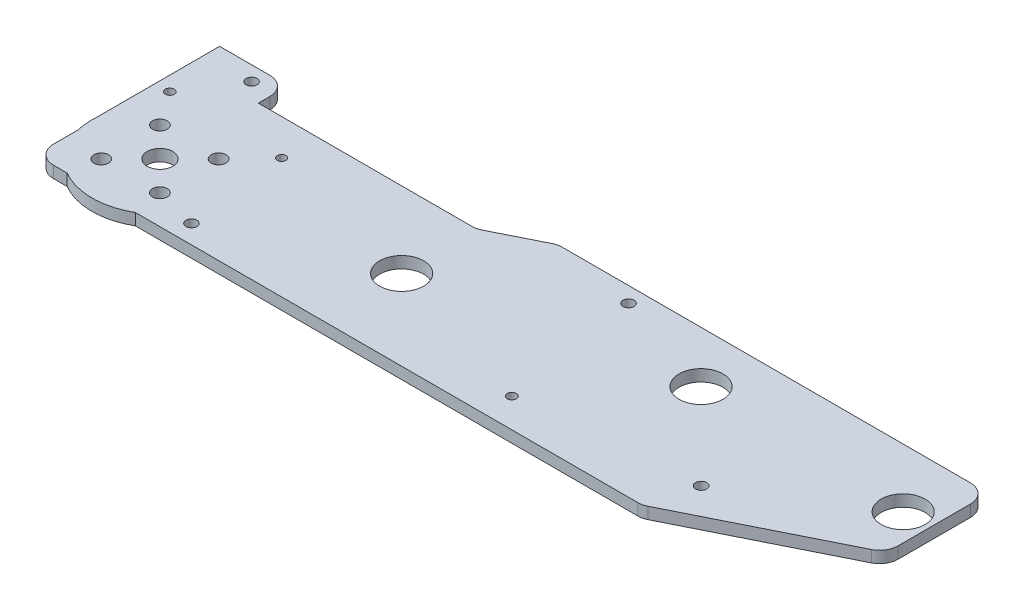
SolidWorks part; units mm, degrees
ref_plane "Front" through (0, 0, 0) normal (0, 0, 1) x (1, 0, 0)
ref_plane "Top" through (0, 0, 0) normal (0, 1, 0) x (1, 0, 0)
ref_plane "Right" through (0, 0, 0) normal (1, 0, 0) x (0, 0, -1)
sketch "Sketch1" plane through (0, 0, 0) normal (0, 1, 0) x (1, 0, 0)
  line L1 (0, 0) -> (210, 0)
  line L2 (0, 0) -> (0, -50)
  line L3 (0, -50) -> (210, -50)
  line L4 (210, 0) -> (210, -50)
  circle A7 centre (3.4895, -16.7877) radius 1.2117
  circle A8 centre (34.3726, -17.194) radius 1.1656
  circle A9 centre (37.5207, -44.9212) radius 1.5
  circle A10 centre (122, -42.0581) radius 1.25
  circle A12 centre (168.9752, -37.4032) radius 1.5173
  circle A13 centre (18, -34) radius 3.4
  dimension "D1" = 210
  dimension "D2" = 50
extrude "Boss-Extrude1" add sketch "Sketch1" along normal blind 3.175
sketch "Sketch2" plane through (0, 3.175, 0) normal (0, 1, 0) x (1, 0, 0)
  line L0 (210, 0) -> (0, 0) construction
  line L1 (0, 0) -> (0, -50) construction
  circle A0 centre (10, -26) radius 2
  circle A1 centre (10, -42) radius 2
  circle A2 centre (26, -26) radius 2
  circle A3 centre (26, -42) radius 2
  dimension "D1" = 16
  dimension "D2" = 16
  dimension "D3" = 16
  dimension "D4" = 26
  dimension "D5" = 10
  dimension "D6" = 10
  dimension "D7" = 26
  dimension "D8" = 16
extrude "Cut-Extrude1" cut sketch "Sketch2" against normal blind 10
sketch "Sketch3" plane through (0, 3.175, 0) normal (0, 1, 0) x (1, 0, 0)
  line L0 (210, 0) -> (0, 0) construction
  line L1 (210, 0) -> (0, 0) construction
  circle A0 centre (78.0103, -28.1) radius 6
  circle A1 centre (145.5313, -14) radius 6
  circle A2 centre (18, -34) radius 0.587
  circle A3 centre (26, -26) radius 2 construction
  circle A4 centre (202.6463, -16) radius 6
  dimension "D1" = 28.1
  dimension "D3" = 16
  dimension "D4" = 14
  dimension "D7" = 125.222
  dimension "D2" = 60.2996
  dimension "D5" = 8
  dimension "D6" = 8
  dimension "D8" = 57.15
extrude "Cut-Extrude2" cut sketch "Sketch3" against normal blind 57.15
sketch "Sketch4" [suppressed] plane through (0, 3.175, 0) normal (0, 1, 0) x (1, 0, 0)
  line L0 (3.4895, -16.7877) -> (18, -34)
  line L1 (3.4895, -20.6627) -> (5.9498, -23.5811)
  line L2 (18, -34) -> (34.3726, -17.194)
  line L3 (34.3726, -17.194) -> (75.8499, -28.1)
  line L4 (75.8499, -28.1) -> (37.5207, -44.9212)
  line L5 (7.3432, -17.194) -> (9.8664, -20.303)
  circle A0 centre (18, -34) radius 15.9299
  circle A1 centre (3.4895, -16.7877) radius 3.8751
  circle A2 centre (34.3726, -17.194) radius 3.7227
  circle A3 centre (37.5207, -44.9212) radius 3.8676
  circle A4 centre (75.8499, -28.1) radius 12.797
  circle A5 centre (112.3021, -4.7393) radius 5.1588
  circle A6 centre (118.879, -40.0177) radius 4.9035
  circle A7 centre (140.772, -16) radius 12.6375
  circle A8 centre (168.9752, -37.4032) radius 4.2066
  circle A9 centre (197.922, -16) radius 12.8
sketch "Sketch5" [suppressed] plane through (0, 3.175, 0) normal (0, 1, 0) x (1, 0, 0)
  line L0 (210, 0) -> (0, 0) construction
  line L2 (-0.6266, -16.7877) -> (37.5207, -16.7877)
  line L3 (-0.6266, -16.7877) -> (-0.6266, -44.9212)
  line L4 (-0.6266, -44.9212) -> (37.5207, -44.9212)
  line L5 (37.5207, -16.7877) -> (37.5207, -44.9212)
  line L6 (75.8499, -15.182) -> (37.5207, -15.182)
  line L7 (75.8499, -15.182) -> (75.8499, -44.9212)
  line L8 (75.8499, -44.9212) -> (37.5207, -44.9212)
  line L9 (37.5207, -15.182) -> (37.5207, -44.9212)
  line L10 (112.3021, -4.7393) -> (75.8499, -4.7393)
  line L11 (112.3021, -4.7393) -> (112.3021, -44.9212)
  line L12 (112.3021, -44.9212) -> (75.8499, -44.9212)
  line L13 (75.8499, -4.7393) -> (75.8499, -44.9212)
  line L14 (112.3021, -4.7393) -> (102.3945, -4.7393)
  line L16 (112.3021, -4.7393) -> (112.3021, 0)
  line L17 (112.3021, 0) -> (102.3945, 0)
  line L18 (102.3945, -4.7393) -> (102.3945, 0)
  line L19 (210, -50) -> (210, 0) construction
  line L20 (112.3021, -4.7393) -> (123.1553, -4.7393)
  line L21 (112.3021, -4.7393) -> (112.3021, 0)
  line L22 (112.3021, 0) -> (123.1553, 0)
  line L23 (123.1553, -4.7393) -> (123.1553, 0)
  line L24 (112.3021, -4.7393) -> (140.772, -4.7393)
  line L25 (112.3021, -4.7393) -> (112.3021, -40.0177)
  line L26 (112.3021, -40.0177) -> (140.772, -40.0177)
  line L27 (140.772, -4.7393) -> (140.772, -40.0177)
  line L28 (140.772, -16) -> (168.9752, -16)
  line L29 (140.772, -16) -> (140.772, -40.0177)
  line L30 (140.772, -40.0177) -> (168.9752, -40.0177)
  line L31 (168.9752, -16) -> (168.9752, -40.0177)
  line L32 (168.9752, -4.7393) -> (210, -4.7393)
  line L33 (168.9752, -4.7393) -> (168.9752, -40.0177)
  line L34 (168.9752, -40.0177) -> (210, -40.0177)
  line L35 (210, -4.7393) -> (210, -40.0177)
  line L36 (0, -50) -> (210, -50) construction
  line L37 (160.7629, -40.0177) -> (177.2091, -40.0177)
  line L38 (160.7629, -40.0177) -> (160.7629, -44.9212)
  line L39 (160.7629, -44.9212) -> (177.2091, -44.9212)
  line L40 (177.2091, -40.0177) -> (177.2091, -44.9212)
  line L41 (112.3021, -40.0177) -> (126.3591, -40.0177)
  line L42 (112.3021, -40.0177) -> (112.3021, -47.7828)
  line L43 (112.3021, -47.7828) -> (126.3591, -47.7828)
  line L44 (126.3591, -40.0177) -> (126.3591, -47.7828)
  line L45 (30.5963, -44.9212) -> (44.6115, -44.9212)
  line L46 (30.5963, -44.9212) -> (30.5963, -50)
  line L47 (30.5963, -50) -> (44.6115, -50)
  line L48 (44.6115, -44.9212) -> (44.6115, -50)
  line L50 (-0.6266, -44.9212) -> (30.5963, -44.9212)
  line L51 (-0.6266, -44.9212) -> (-0.6266, -50)
  line L52 (-0.6266, -50) -> (30.5963, -50)
  line L53 (30.5963, -44.9212) -> (30.5963, -50)
  circle A0 centre (3.4895, -16.7877) radius 4.1161
  circle A1 centre (34.3726, -17.194) radius 3.8132
  circle A2 centre (75.8499, -28.1) radius 12.918
  circle A3 centre (112.3021, -4.7393) radius 5.2663
  circle A4 centre (140.772, -16) radius 13.0245
  circle A5 centre (197.922, -16) radius 12.3805
  circle A6 centre (168.9752, -37.4032) radius 4.7643
  circle A7 centre (118.879, -40.0177) radius 5.279
  circle A8 centre (37.5207, -44.9212) radius 4.2049
  line M12 (0, 0) -> (0, -50)
  line M13 (0, -50) -> (210, -50)
  line M14 (210, -50) -> (210, 0)
  line M15 (210, 0) -> (0, 0)
extrude "Cut-Extrude5" [suppressed] cut sketch "Sketch5" against normal blind 11.52 contours A5 L32 L23 L24 A4 L28 L33 M14 M15 | A1 L6 L13 L10 L18 A0 L2 M15 M12 | L8 L48 L34 L40 L39 L38 L30 L26 L44 L43 L42 L12 M13 M14
fillet "Fillet1" [suppressed] radius 5
sketch "Sketch10" plane through (0, 3.175, 0) normal (0, 1, 0) x (1, 0, 0)
  line L0 (210, -27.8594) -> (165.5029, -50)
  line L1 (210, -50) -> (210, 0) construction
  line L2 (0, -50) -> (210, -50) construction
  line L3 (165.5029, -50) -> (210, -50)
  line L4 (210, -50) -> (210, -27.8594)
  line L5 (92.5326, 0) -> (77.6548, -7.4028)
  line L6 (210, 0) -> (0, 0) construction
  line L7 (77.6548, -7.4028) -> (0, -7.4028)
  line L8 (0, 0) -> (0, -50) construction
  line L9 (0, -7.4028) -> (0, 0)
  line L10 (0, 0) -> (92.5326, 0)
extrude "Cut-Extrude7" cut sketch "Sketch10" against normal blind 10
fillet "Fillet3" radius 5 5 edges at (77.6548, 1.5875, 7.4028) (92.5326, 1.5875, 0) (210, 1.5875, 0) (210, 1.5875, 27.8594) (165.5029, 1.5875, 50)
sketch "Sketch11" plane through (0, 3.175, 0) normal (0, 1, 0) x (1, 0, 0)
  circle A0 centre (18, -34) radius 18.5
  circle A1 centre (10, -26) radius 2
  circle A2 centre (10, -42) radius 2
  circle A3 centre (26, -26) radius 2
  circle A4 centre (26, -42) radius 2
extrude "Boss-Extrude4" add sketch "Sketch11" against normal blind 3.175
sketch "Sketch16" plane through (0, 0, 7.4028) normal (0, 0, -1) x (-1, 0, 0)
  line L0 (0, 3.175) -> (-76.4796, 3.175) construction
  line L1 (0, 0) -> (-18.2576, 0)
  line L2 (0, 0) -> (0, 3.175)
  line L3 (0, 3.175) -> (-18.2576, 3.175)
  line L4 (-18.2576, 0) -> (-18.2576, 3.175)
extrude "Boss-Extrude7" add sketch "Sketch16" along normal blind 8.128
sketch "Sketch17" plane through (0, 0, 0) normal (-1, 0, 0) x (0, 0, 1)
  line L0 (-0.7252, 3.175) -> (29.728, 3.175) construction
  line L1 (-0.7252, 0) -> (32.5748, 0)
  line L2 (-0.7252, 0) -> (-0.7252, 3.175)
  line L3 (-0.7252, 3.175) -> (32.5748, 3.175)
  line L4 (32.5748, 0) -> (32.5748, 3.175)
  dimension "D1" = 33.3
extrude "Boss-Extrude8" add sketch "Sketch17" along normal blind 35.56
sketch "Sketch18" plane through (0, 3.175, 0) normal (0, 1, 0) x (1, 0, 0)
  line L0 (-35.56, 0.7252) -> (18.2576, 0.7252) construction
  circle A0 centre (-21.4859, -15.9248) radius 11.315
  circle A1 centre (-29.612, -23.7985) radius 2
  circle A2 centre (-29.3597, -7.7987) radius 2
  circle A3 centre (-13.3598, -8.0511) radius 2
  circle A4 centre (-13.6122, -24.0509) radius 2
  circle A5 centre (-21.4859, -15.9248) radius 4
  point P15 (-21.4859, -15.9248)
  dimension "D1" = 22.63
  dimension "D3" = 4
  dimension "D2" = 16.65
extrude "Cut-Extrude8" cut sketch "Sketch18" against normal blind 9 contours A2 | A1 | A4 | A3
sketch "Sketch19" plane through (0, 3.175, 0) normal (0, 1, 0) x (1, 0, 0)
  circle A0 centre (-21.3597, -15.7987) radius 4
  circle A1 centre (-29.3597, -7.7987) radius 2 construction
  dimension "D1" = 8
  dimension "D2" = 8
extrude "Cut-Extrude9" cut sketch "Sketch19" against normal blind 40
fillet "Fillet4" radius 5 4 edges at (0, 1.5875, 50) (18.2576, 1.5875, -0.7252) (-35.56, 1.5875, -0.7252) (-35.56, 1.5875, 32.5748)
sketch "Sketch20" plane through (0, 3.175, 0) normal (0, 1, 0) x (1, 0, 0)
  circle A0 centre (18, -34) radius 3.5
  circle A1 centre (10, -26) radius 2 construction
  dimension "D1" = 8
  dimension "D2" = 8
extrude "Cut-Extrude10" cut sketch "Sketch20" against normal blind 10
sketch "Sketch21" plane through (0, 3.175, 0) normal (0, 1, 0) x (1, 0, 0)
  line L0 (210, -24.7625) -> (210, -5) construction
  circle A0 centre (116, -4.2372) radius 1.5
  dimension "D1" = 94
extrude "Cut-Extrude11" cut sketch "Sketch21" against normal blind 10
sketch "Sketch22" plane through (0, 3.175, 0) normal (0, 1, 0) x (1, 0, 0)
  line L0 (18.2576, -4.2748) -> (18.2576, -7.4028) construction
  line L1 (-30.56, 0.7252) -> (13.2576, 0.7252) construction
  circle A0 centre (12.2576, -3.2748) radius 1.5
  dimension "D1" = 6
  dimension "D2" = 4
extrude "Cut-Extrude12" cut sketch "Sketch22" against normal blind 10
sketch "Sketch24" plane through (0, 3.175, 0) normal (0, 1, 0) x (1, 0, 0)
  line L0 (-30.56, 0.7252) -> (13.2576, 0.7252) construction
  line L1 (-35.56, -27.5748) -> (-35.56, -4.2748) construction
  circle A0 centre (-30.56, -15.7748) radius 1.5
  dimension "D1" = 16.5
  dimension "D2" = 5
extrude "Cut-Extrude13" cut sketch "Sketch24" against normal blind 10
sketch "Sketch25" plane through (0, 3.175, 0) normal (0, 1, 0) x (1, 0, 0)
  line L0 (-0.445, -32.5748) -> (-0.445, 13.8362)
  line L1 (-0.445, 13.8362) -> (-50.2273, 13.8362)
  line L2 (-50.2273, 13.8362) -> (-50.2273, -32.5748)
  line L3 (-50.2273, -32.5748) -> (-0.445, -32.5748)
extrude "Cut-Extrude14" cut sketch "Sketch25" against normal blind 10
